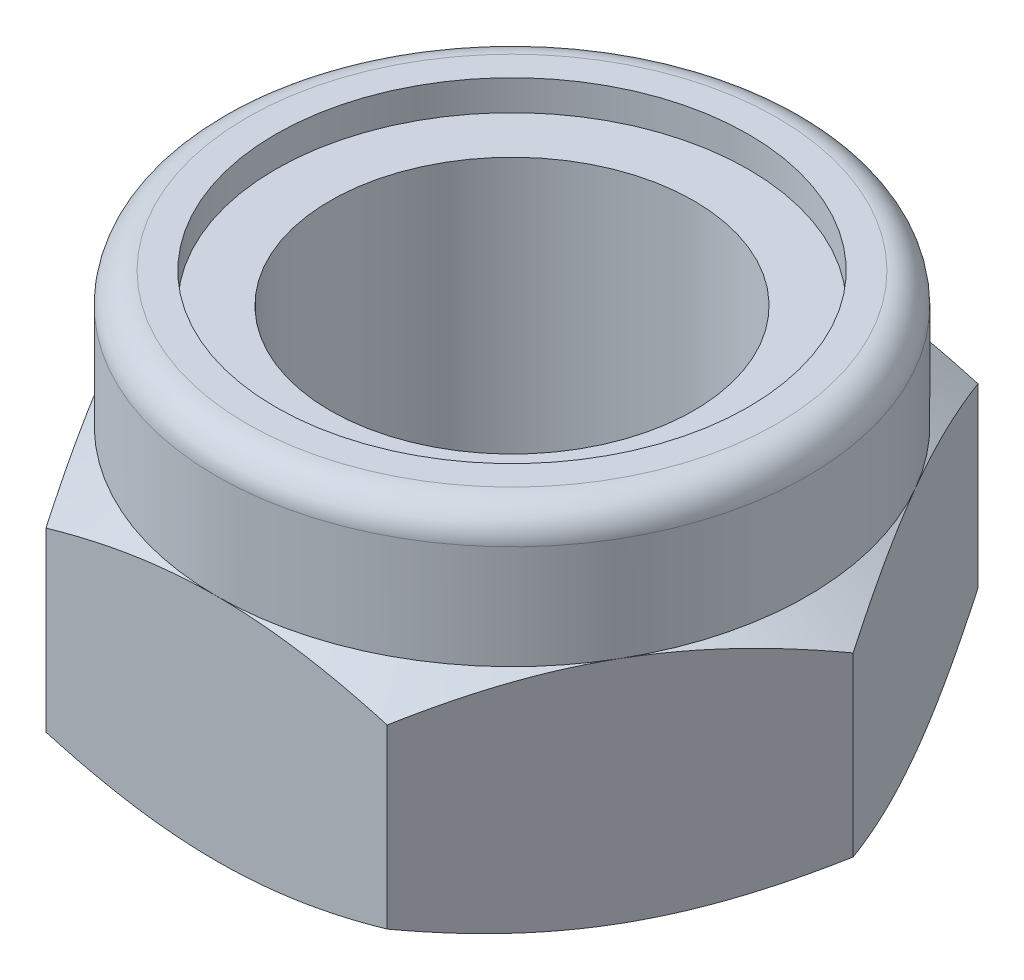
SolidWorks part; units mm, degrees
ref_plane "Front Plane" through (0, 0, 0) normal (0, 0, 1) x (1, 0, 0)
ref_plane "Top Plane" through (0, 0, 0) normal (0, 1, 0) x (1, 0, 0)
ref_plane "Right Plane" through (0, 0, 0) normal (1, 0, 0) x (0, 0, -1)
sketch "Sketch1" plane through (0, 0, 0) normal (0, 1, 0) x (1, 0, 0)
  line L0 (-8.8, 0) -> (8.8, 0) construction
  line L1 (3.7528, 6.5) -> (-3.7528, 6.5)
  line L2 (-3.7528, 6.5) -> (-7.5056, 0)
  line L3 (-7.5056, 0) -> (-3.7528, -6.5)
  line L4 (-3.7528, -6.5) -> (3.7528, -6.5)
  line L5 (3.7528, -6.5) -> (7.5056, 0)
  line L6 (7.5056, 0) -> (3.7528, 6.5)
  circle A0 centre (0, 0) radius 6.5 construction
extrude "Extrude1" add sketch "Sketch1" along normal mid plane 5.05
sketch "Sketch2" plane through (0, 0, 0) normal (0, 0, 1) x (1, 0, 0)
  line L0 (7.5056, 2.525) -> (6.5, 2.525)
  line L1 (3.7528, 2.525) -> (7.5056, 2.525) construction
  line L2 (6.5, 2.525) -> (7.5056, 1.9444)
  line L3 (7.5056, 2.525) -> (7.5056, -2.525) construction
  line L4 (7.5056, 1.9444) -> (7.5056, 2.525)
  line L5 (0, -8.8) -> (0, 8.8) construction
  dimension "D2" = 30
ref_axis "Axis1" through (0, 2.75, 0) along (0, -1, 0)
revolve "Cut-Revolve1" cut sketch "Sketch2" angle 360 about axis through (0, 2.75, 0) along (0, -1, 0)
mirror "Mirror1" about plane through (0, 0, 0) normal (0, 1, 0) of "Cut-Revolve1"
sketch "Sketch3" plane through (0, 0, 0) normal (0, 0, 1) x (1, 0, 0)
  line L0 (0, 2.525) -> (0, 4.8083)
  line L2 (6.5, 2.525) -> (6.5, 4.8083)
  line L3 (5.8333, 5.475) -> (5.2, 5.475)
  line L4 (6.5, 2.525) -> (0, 2.525)
  line L5 (0, -2.525) -> (5.6292, -2.525) construction
  line L6 (5.2, 5.475) -> (5.2, 4.8083)
  line L7 (5.2, 4.8083) -> (0, 4.8083)
  line L8 (0, 2.75) -> (0, -2.75) construction
  arc A0 (6.5, 4.8083) -> (5.8333, 5.475) centre (5.8333, 4.8083) ccw
revolve "Revolve1" add sketch "Sketch3" angle 360 about axis through (0, 2.75, 0) along (0, -1, 0)
sketch "Sketch4" plane through (0, -2.525, 0) normal (0, -1, 0) x (1, 0, 0)
  circle A0 centre (0, 0) radius 4
extrude "Cut-Extrude1" cut sketch "Sketch4" against normal up to next
equation "\"D1@Sketch2\" =( \"D1@Sketch1\"/2)"
equation "\"D3@Sketch3\" =(\"D1@Sketch1\"/2) * 0.8"
equation "\"D1@Sketch3\" =\"D1@Sketch4\" * 0.08333333333333"
